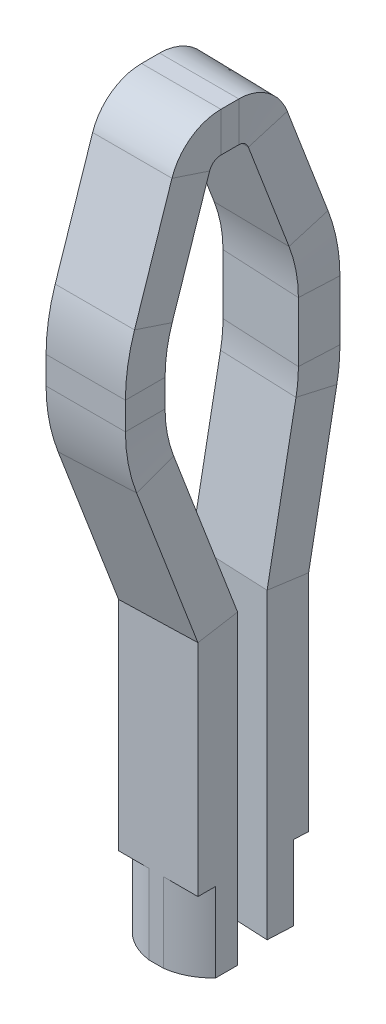
SolidWorks part; units mm, degrees
ref_plane "Alzado" through (0, 0, 0) normal (0, 0, 1) x (1, 0, 0)
ref_plane "Planta" through (0, 0, 0) normal (0, 1, 0) x (1, 0, 0)
ref_plane "Vista lateral" through (0, 0, 0) normal (1, 0, 0) x (0, 0, -1)
sketch "Croquis2" plane through (0, 0, 0) normal (0, 1, 0) x (1, 0, 0)
  line L1 (0, 0) -> (5, 0)
  line L2 (0, 0) -> (0, -2.5)
  line L3 (0, -2.5) -> (5, -2.5)
  line L4 (5, 0) -> (5, -2.5)
  dimension "D1" = 5
  dimension "D2" = 2.5
extrude "Saliente-Extruir1" add sketch "Croquis2" along normal blind 5
sketch3d "Croquis3D1"
  line L0 (2.5, 5, 0) -> (2.5, 5, 2.5) construction
  line L1 (5, 5, 0) -> (0, 5, 0) construction
  line L2 (0, 5, 2.5) -> (5, 5, 2.5) construction
  line L3 (2.5, 5, 1.25) -> (2.5, 19, 1.25)
  line L4 (2.5, 19, 1.25) -> (1.936, 28.679, 4.6049)
  line L5 (1.8422, 31.9949, 5.1629) -> (1.8422, 33.7223, 5.1629)
  line L6 (1.8422, 36.8775, 4.6521) -> (1.8422, 43.9723, 2.2931)
  line L7 (1.8422, 45.3413, 0.3952) -> (1.8422, 45.3413, -0.7378)
  line L8 (1.9205, 43.9976, -2.6278) -> (2.2894, 37.6661, -4.8225)
  line L9 (2.3832, 34.3501, -5.3804) -> (2.3832, 30.5844, -5.3804)
  line L10 (2.3832, 28.7245, -5.2059) -> (2.3832, 19.2342, -3.4095)
  line L11 (2.3832, 19.2342, -3.4095) -> (2.3832, 0.2792, -3.4095)
  arc A0 (2.3832, 30.5844, -5.3804) -> (2.3832, 28.7245, -5.2059) centre (2.3832, 30.5844, 4.6196) ccw
  arc A1 (2.2894, 37.6661, -4.8225) -> (2.3832, 34.3501, -5.3804) centre (0.7255, 34.3501, 4.4812) ccw
  arc A2 (1.8422, 33.7223, 5.1629) -> (1.8422, 36.8775, 4.6521) centre (1.8422, 33.7223, -4.8371) ccw
  arc A3 (1.936, 28.679, 4.6049) -> (1.8422, 31.9949, 5.1629) centre (3.5, 31.9949, -4.6988) ccw
  arc A4 (1.8422, 45.3413, -0.7378) -> (1.9205, 43.9976, -2.6278) centre (1.9586, 43.3447, -0.7378) ccw
  arc A5 (1.8422, 43.9723, 2.2931) -> (1.8422, 45.3413, 0.3952) centre (1.8422, 43.3413, 0.3952) ccw
  point P16 (3.5, 0.2792, -3.3295)
  point P17 (3.5, 19.2342, -3.4095)
  point P20 (2.3832, 29.6463, -5.3804)
  point P21 (-7.6168, 30.5844, 4.6196)
  point P24 (2.3832, 36.0564, -5.3804)
  point P25 (-9.1362, 34.3501, 2.8234)
  point P28 (1.8422, 35.3413, 5.1629)
  point P29 (-8.1578, 33.7223, -4.8371)
  point P32 (1.8422, 30.2887, 5.1629)
  point P33 (-6.3616, 31.9949, -6.3565)
  point P36 (1.8422, 45.3413, -2.1621)
  point P37 (-0.038, 43.2283, -0.7378)
  point P40 (1.8422, 45.3413, 1.8379)
  point P41 (-0.1578, 43.3413, 0.3952)
  dimension "D3" = 10
  dimension "D4" = 2
  dimension "D1" = 14
  dimension "D2" = 4
sketch "Croquis3" plane through (0, 5, 0) normal (0, 1, 0) x (1, 0, 0)
  line L1 (0, -2.5) -> (5, -2.5)
  line L2 (0, -2.5) -> (0, 0)
  line L3 (0, 0) -> (5, 0)
  line L4 (5, -2.5) -> (5, 0)
sweep "Barrer1" add profiles "Croquis3" path "Croquis3D1"
sketch "Croquis5" plane through (0, 0, 0) normal (0, -1, 0) x (1, 0, 0)
  circle A0 centre (2.3692, -1.0701) radius 3.5992
  circle A1 centre (2.3692, -1.0701) radius 8.8156
extrude "Cortar-Extruir2" cut sketch "Croquis5" against normal blind 5
